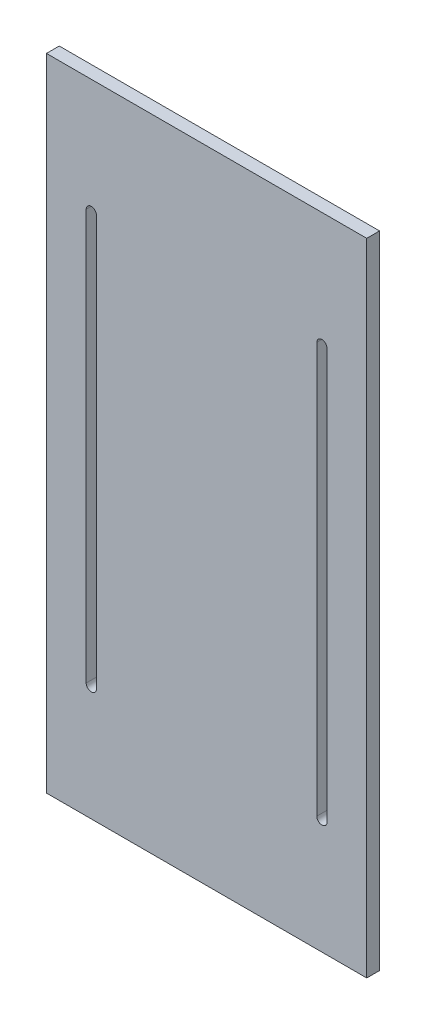
SolidWorks part; units mm, degrees
ref_plane "Front Plane" through (0, 0, 0) normal (0, 0, 1) x (1, 0, 0)
ref_plane "Top Plane" through (0, 0, 0) normal (0, 1, 0) x (1, 0, 0)
ref_plane "Right Plane" through (0, 0, 0) normal (1, 0, 0) x (0, 0, -1)
sketch "Sketch1" plane through (0, 0, 0) normal (0, 0, 1) x (1, 0, 0)
  line L1 (-25, -50) -> (25, -50)
  line L2 (-25, -50) -> (-25, 50)
  line L3 (-25, 50) -> (25, 50)
  line L4 (25, -50) -> (25, 50)
  line L5 (-25, -50) -> (25, 50) construction
  line L6 (-25, 50) -> (25, -50) construction
  point P0 (0, 0)
  dimension "D1" = 50
  dimension "D2" = 100
extrude "Boss-Extrude1" add sketch "Sketch1" along normal blind 2
sketch "Sketch2" plane through (0, 0, 0) normal (0, 0, -1) x (-1, 0, 0)
  line L0 (1.1, 0) -> (-1.1, 0) construction
  line L1 (-18.8, 0) -> (-17.2, 0)
  line L2 (-18.8, 0) -> (-18.8, 32.022)
  line L4 (-17.2, 0) -> (-17.2, 32.022)
  line L5 (0, 1.1) -> (0, -1.1) construction
  arc A0 (-18.8, 32.022) -> (-17.2, 32.022) centre (-18, 32.022) cw
  dimension "D2" = 0.8
  dimension "D1" = 18.8
extrude "Cut-Extrude1" cut sketch "Sketch2" against normal through all
pattern_linear "LPattern1" count 2 spacing 36 along (-1, 0, 0) of "Cut-Extrude1"
mirror "Mirror1" about plane through (0, 0, 0) normal (0, 1, 0) of "LPattern1", "Cut-Extrude1"
